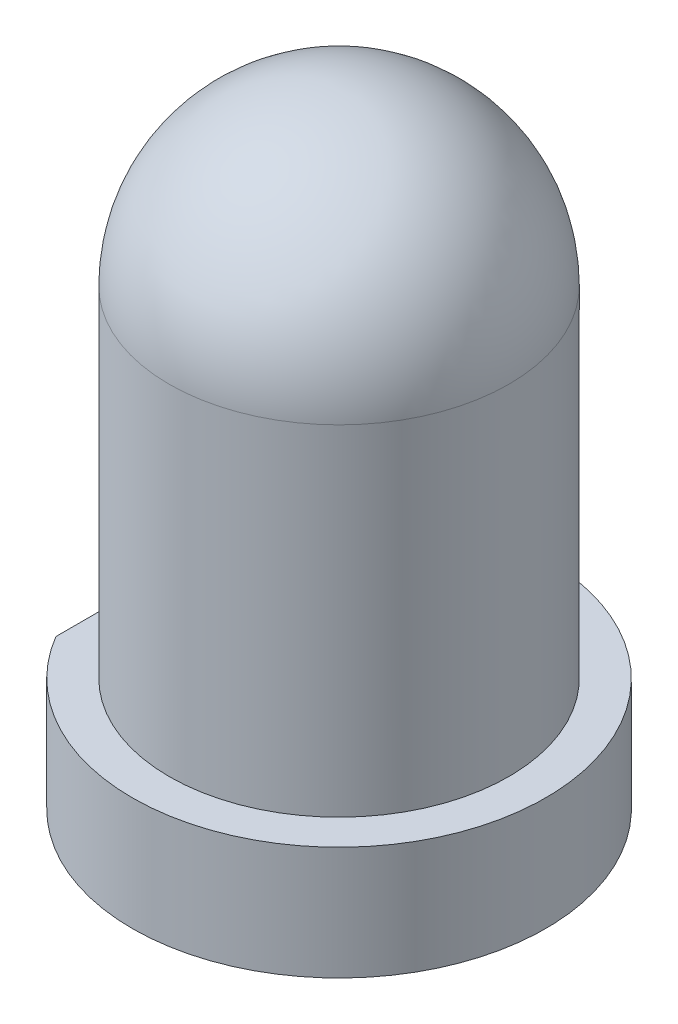
SolidWorks part; units mm, degrees
ref_plane "Front Plane" through (0, 0, 0) normal (0, 0, 1) x (1, 0, 0)
ref_plane "Top Plane" through (0, 0, 0) normal (0, 1, 0) x (1, 0, 0)
ref_plane "Right Plane" through (0, 0, 0) normal (1, 0, 0) x (0, 0, -1)
sketch "Sketch1" plane through (0, 0, 0) normal (0, 0, 1) x (1, 0, 0)
  line L0 (0, 5.8312) -> (0, -0.7607) construction
  line L1 (0, 0) -> (1.825, 0)
  line L2 (1.825, 0) -> (1.825, 1)
  line L3 (1.825, 1) -> (1.5, 1)
  line L4 (1.5, 1) -> (1.5, 4)
  line L5 (0, 0) -> (0, 5.5)
  arc A0 (1.5, 4) -> (0, 5.5) centre (0, 4) ccw
  point P10 (0, 5.8312)
  point P11 (0, -0.7607)
  dimension "D1" = 3
  dimension "D2" = 3.65
  dimension "D3" = 5.5
  dimension "D4" = 1
revolve "Revolve1" add sketch "Sketch1" angle 360 about L0
sketch "Sketch2" plane through (0, 0, 0) normal (0, 1, 0) x (1, 0, 0)
  line L0 (-1.5709, 1.3899) -> (-1.5709, -1.6041)
  line L1 (-1.5709, -1.6041) -> (-2.6267, -0.2678)
  line L2 (-2.6267, -0.2678) -> (-1.5709, 1.3899)
extrude "Cut-Extrude2" cut sketch "Sketch2" against normal blind 10 and the other way through all
